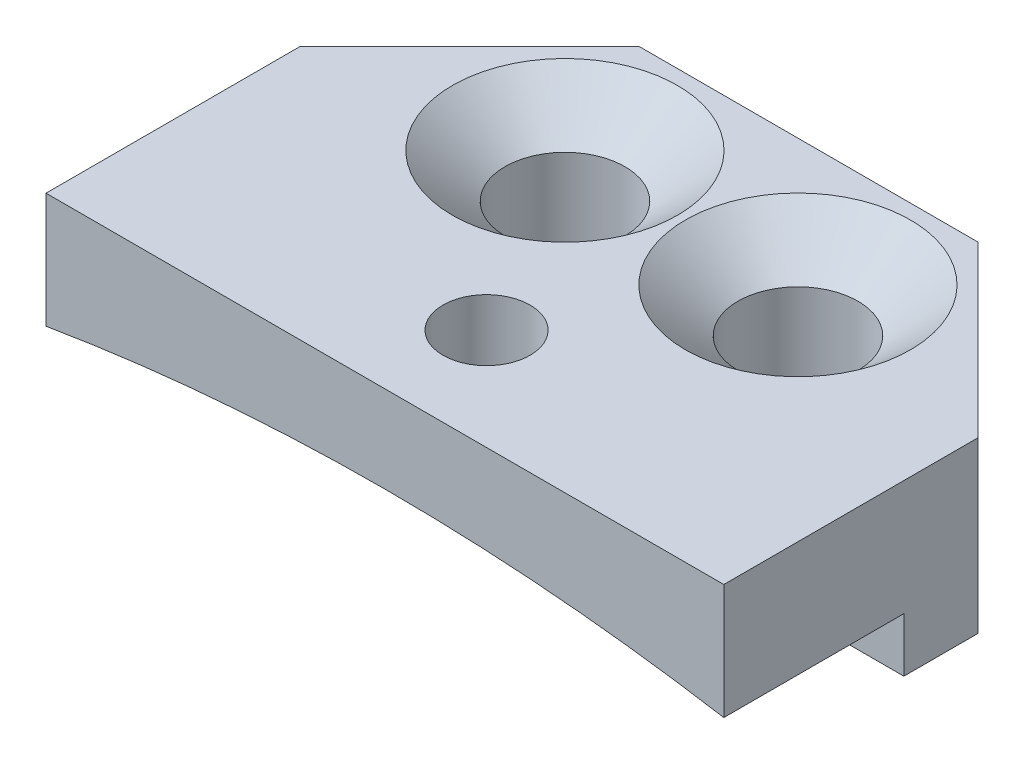
SolidWorks part; units mm, degrees
ref_plane "Front Plane" through (0, 0, 0) normal (0, 0, 1) x (1, 0, 0)
ref_plane "Top Plane" through (0, 0, 0) normal (0, 1, 0) x (1, 0, 0)
ref_plane "Right Plane" through (0, 0, 0) normal (1, 0, 0) x (0, 0, -1)
sketch "Sketch1" plane through (0, 0, 0) normal (0, 1, 0) x (1, 0, 0)
  line L0 (-12.7, 7.9375) -> (12.7, -7.9375) construction
  line L1 (-12.7, 7.9375) -> (12.7, 7.9375)
  line L2 (-12.7, 7.9375) -> (-12.7, -7.9375)
  line L3 (-12.7, -7.9375) -> (12.7, -7.9375)
  line L4 (12.7, 7.9375) -> (12.7, -7.9375)
  point P4 (0, 0)
  dimension "D1" = 15.875
  dimension "D2" = 25.4
extrude "Boss-Extrude1" add sketch "Sketch1" along normal blind 6.35
chamfer "Chamfer1" distance 6.35 angle 45 2 edges at (12.7, 3.175, -7.9375) (-12.7, 3.175, -7.9375)
sketch "Sketch2" plane through (0, 0, 7.9375) normal (0, 0, 1) x (1, 0, 0)
  line L0 (-2.7178, 3.048) -> (-2.7178, 0) construction
  line L1 (-2.7178, 0) -> (2.7178, 0) construction
  line L2 (2.7178, 3.048) -> (2.7178, 0) construction
  line L3 (-12.7, 0) -> (12.7, 0) construction
  line L4 (-12.7, 2.0307) -> (12.7, 2.0307) construction
  line L5 (-12.7, 2.0307) -> (-12.7, 0)
  line L6 (-12.7, 0) -> (12.7, 0)
  line L7 (12.7, 0) -> (12.7, 2.0307)
  arc A0 (-12.7, 2.0307) -> (12.7, 2.0307) centre (0, -73.1035) cw
  point P7 (0, 0)
  point P9 (2.8834, 2.9284)
  point P12 (0, 0)
  point P15 (-2.2518, 2.9862)
  dimension "D2" = 76.2
  dimension "D1" = 5.4356
  dimension "D3" = 25.4
  dimension "D4" = 3.048
extrude "Cut-Extrude1" cut sketch "Sketch2" against normal blind 6.7469
sketch "Sketch3" plane through (0, 6.35, 0) normal (0, 1, 0) x (1, 0, 0)
  circle A0 centre (0, -4.1293) radius 1.6319 construction
  circle A1 centre (0, -4.1293) radius 1.6319
extrude "Cut-Extrude2" cut sketch "Sketch3" against normal through all
hole_wizard "CSK for #8 Flat Head Machine Screw (100)1" positions "Sketch4" profile "Sketch5" countersink size "#8" standard "ANSI Inch" end condition through all
sketch "Sketch4" plane through (0, 6.35, 0) normal (0, 1, 0) x (1, 0, 0)
  line L0 (0, 7.9375) -> (0, -1.7163) construction
  line L2 (6.35, 7.9375) -> (-6.35, 7.9375) construction
  point P2 (-4.3656, 3.175)
  point P18 (0, 0)
  point P21 (0, 0)
  point P22 (0, 0)
  point P23 (0, 0)
  point P24 (4.3656, 3.175)
  dimension "D2" = 4.7625
  dimension "D1" = 4.3656
sketch "Sketch5" plane through (-4.3656, 6.35, -3.175) normal (1, 0, 0) x (0, 0, 1)
  line L0 (0, 0) -> (0, 6.35)
  line L1 (0, 6.35) -> (2.2479, 6.35)
  line L2 (2.2479, 6.35) -> (2.2479, 1.6518)
  line L3 (2.2479, 1.6518) -> (4.2164, 0)
  line L5 (4.2164, 0) -> (0, 0)
  line L6 (-2.2479, 1.6518) -> (-4.2164, 0) construction
  line L11 (0, -6.35) -> (0, 107.95) construction
  dimension "Thru Hole Dia." = 4.4958
  dimension "Thru Hole Depth" = 6.35
  dimension "Near C'Sink Dia." = 8.4328
  dimension "Near C'Sink Angle" = 100
